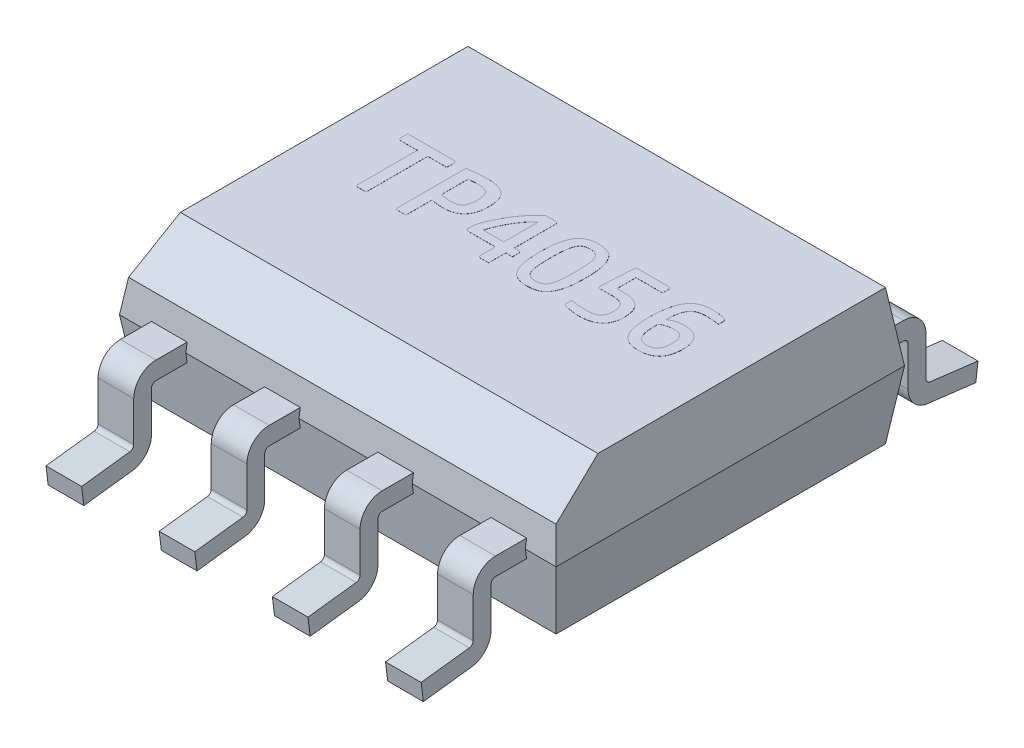
SolidWorks part; units mm, degrees
ref_plane "Front" through (0, 0, 0) normal (0, 0, 1) x (1, 0, 0)
ref_plane "Top" through (0, 0, 0) normal (0, 1, 0) x (1, 0, 0)
ref_plane "Right" through (0, 0, 0) normal (1, 0, 0) x (0, 0, -1)
sketch "Sketch1" plane through (0, 0, 0) normal (0, 1, 0) x (1, 0, 0)
  line L1 (-2.45, -1.955) -> (2.45, -1.955)
  line L2 (-2.45, -1.955) -> (-2.45, 1.955)
  line L3 (-2.45, 1.955) -> (2.45, 1.955)
  line L4 (2.45, -1.955) -> (2.45, 1.955)
  line L5 (-2.45, -1.955) -> (2.45, 1.955) construction
  line L6 (-2.45, 1.955) -> (2.45, -1.955) construction
  point P0 (0, 0)
  dimension "D1" = 4.9
  dimension "D2" = 3.91
extrude "Extrude1" add sketch "Sketch1" along normal mid plane 1.52 draft 8
chamfer "Chamfer1" distance 0.4 angle 45 1 edges at (0, 0.76, 1.8482)
ref_plane "Plane1" through (1.905, 0, 0) normal (1, 0, 0) x (0, 0, -1)
sketch "Sketch5" plane through (1.905, 0, 0) normal (1, 0, 0) x (0, 0, -1)
  line L0 (0, 0.1) -> (-2.29, 0.1)
  line L1 (-2.54, -0.15) -> (-2.54, -0.5955)
  line L2 (-2.5839, -0.6451) -> (-3.1244, -0.7115)
  line L3 (0, -0.1) -> (-2.29, -0.1)
  line L4 (0, 0.1) -> (0, -0.1) construction
  line L5 (-3.1244, -0.7115) -> (-3.1, -0.91)
  line L6 (-2.34, -0.15) -> (-2.34, -0.5955)
  line L7 (-2.5595, -0.8436) -> (-3.1, -0.91)
  line L9 (2.2739, 0) -> (-2.2739, 0) construction
  line L11 (-1.8482, -0.76) -> (1.8482, -0.76) construction
  line L12 (0, 1.2508) -> (0, -1.2508) construction
  line L13 (2.5595, -0.8436) -> (3.1, -0.91)
  line L14 (2.34, -0.15) -> (2.34, -0.5955)
  line L15 (3.1244, -0.7115) -> (3.1, -0.91)
  line L16 (0, -0.1) -> (2.29, -0.1)
  line L17 (2.5839, -0.6451) -> (3.1244, -0.7115)
  line L18 (2.54, -0.15) -> (2.54, -0.5955)
  line L19 (0, 0.1) -> (2.29, 0.1)
  arc A0 (-2.54, -0.5955) -> (-2.5839, -0.6451) centre (-2.59, -0.5955) cw
  arc A1 (-2.29, 0.1) -> (-2.54, -0.15) centre (-2.29, -0.15) ccw
  arc A2 (-2.29, -0.1) -> (-2.34, -0.15) centre (-2.29, -0.15) ccw
  arc A3 (-2.34, -0.5955) -> (-2.5595, -0.8436) centre (-2.59, -0.5955) cw
  arc A4 (2.34, -0.5955) -> (2.5595, -0.8436) centre (2.59, -0.5955) ccw
  arc A5 (2.29, -0.1) -> (2.34, -0.15) centre (2.29, -0.15) cw
  arc A6 (2.29, 0.1) -> (2.54, -0.15) centre (2.29, -0.15) cw
  arc A7 (2.54, -0.5955) -> (2.5839, -0.6451) centre (2.59, -0.5955) ccw
  arc A8 (-2.29, 0.1) -> (-2.54, -0.15) centre (-2.29, -0.15) ccw construction
  arc A9 (-2.54, -0.5955) -> (-2.5839, -0.6451) centre (-2.59, -0.5955) cw construction
  point P13 (-2.3, -0.4503)
  dimension "D6" = 0.15
  dimension "D7" = 0.76
  dimension "D5" = 0.25
  dimension "D1" = 0.2
  dimension "D2" = 0.1
  dimension "D3" = 7
  dimension "D4" = 6.2
extrude "Extrude3" add sketch "Sketch5" along normal mid plane 0.4
pattern_linear "LPattern3" count 4 spacing 1.27 along (-1, 0, 0) of "Extrude3"
sketch "Sketch6" plane through (0, 0.76, 0) normal (0, 1, 0) x (1, 0, 0)
  line L0 (-2.3432, -0.1396) -> (2.3432, -0.1396) construction
  line L1 (-2.3432, 1.8482) -> (-2.3432, -1.3782) construction
  line L2 (2.3432, -1.3782) -> (2.3432, 1.8482) construction
  text T0 "TP4056" font "HP Simplified" height 0.8
extrude "Boss-Extrude1" add sketch "Sketch6" along normal blind 0.001
